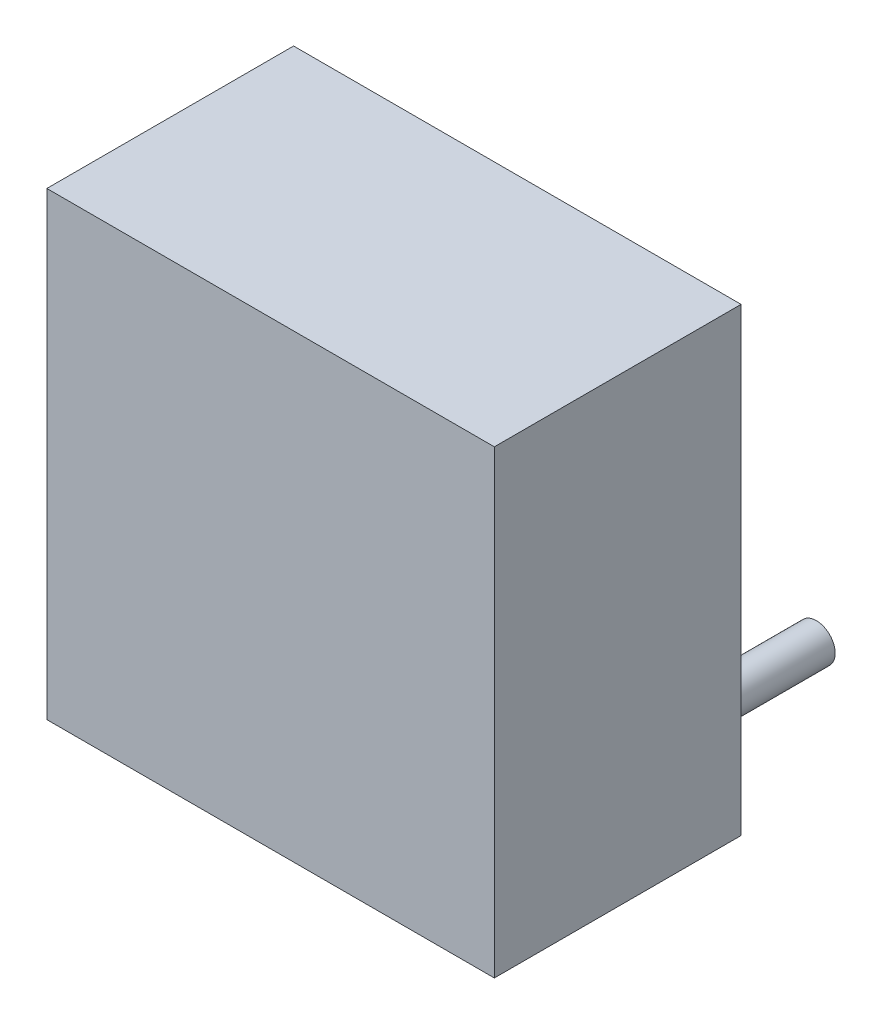
SolidWorks part; units mm, degrees
ref_plane "Front Plane" through (0, 0, 0) normal (0, 0, 1) x (1, 0, 0)
ref_plane "Top Plane" through (0, 0, 0) normal (0, 1, 0) x (1, 0, 0)
ref_plane "Right Plane" through (0, 0, 0) normal (1, 0, 0) x (0, 0, -1)
sketch "Sketch1" plane through (0, 0, 0) normal (0, 0, 1) x (1, 0, 0)
  line L1 (-5.35, -5.5) -> (5.35, -5.5)
  line L2 (-5.35, -5.5) -> (-5.35, 5.5)
  line L3 (-5.35, 5.5) -> (5.35, 5.5)
  line L4 (5.35, -5.5) -> (5.35, 5.5)
  line L5 (-5.35, -5.5) -> (5.35, 5.5) construction
  line L6 (-5.35, 5.5) -> (5.35, -5.5) construction
  point P0 (0, 0)
  dimension "D1" = 10.7
  dimension "D2" = 11
extrude "Boss-Extrude1" add sketch "Sketch1" along normal blind 5.9
sketch "Sketch2" plane through (0, 0, 0) normal (0, 0, -1) x (-1, 0, 0)
  line L0 (-5.35, 5.5) -> (5.35, 5.5) construction
  line L1 (-3.75, -4) -> (-1.25, -4) construction
  circle A0 centre (-3.75, -4) radius 0.45
  circle A1 centre (-1.25, -4) radius 0.45
  circle A2 centre (1.25, -4) radius 0.45
  circle A3 centre (3.75, -4) radius 0.45
  dimension "D1" = 0.9
  dimension "D2" = 3.75
  dimension "D3" = 9.5
  dimension "D5" = 2.5
  dimension "D4" = 4
extrude "Boss-Extrude2" add sketch "Sketch2" along normal blind 3.4
